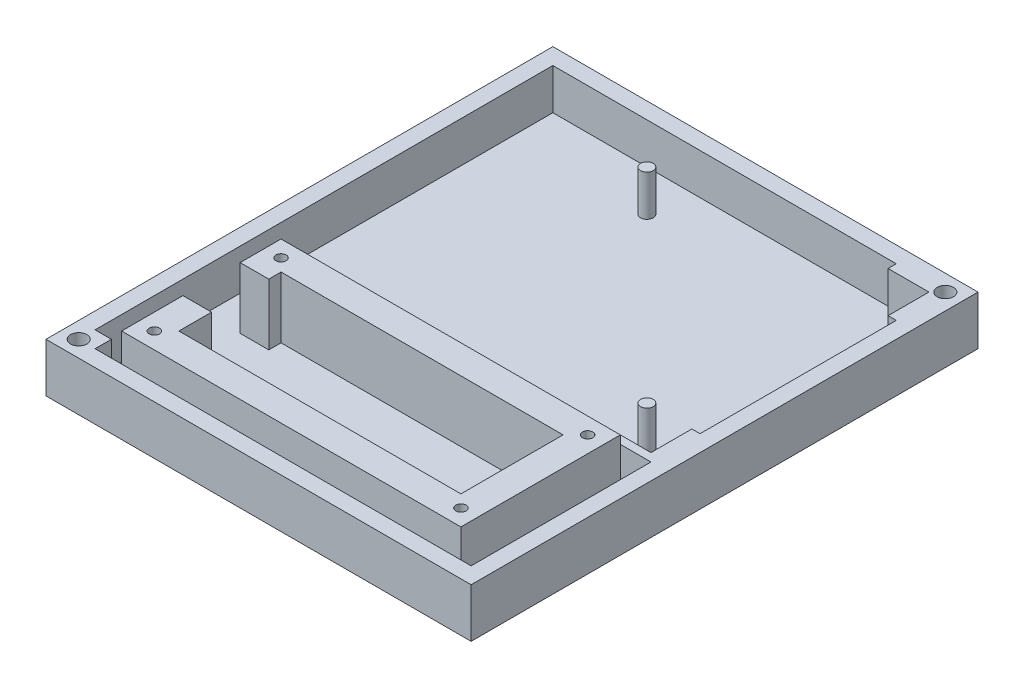
SolidWorks part; units mm, degrees
ref_plane "Front Plane" through (0, 0, 0) normal (0, 0, 1) x (1, 0, 0)
ref_plane "Top Plane" through (0, 0, 0) normal (0, 1, 0) x (1, 0, 0)
ref_plane "Right Plane" through (0, 0, 0) normal (1, 0, 0) x (0, 0, -1)
sketch "Sketch1" plane through (0, 0, 0) normal (0, 1, 0) x (1, 0, 0)
  line L1 (-52, -62) -> (52, -62)
  line L2 (-52, -62) -> (-52, 62)
  line L3 (-52, 62) -> (52, 62)
  line L4 (52, -62) -> (52, 62)
  line L5 (-52, -62) -> (52, 62) construction
  line L6 (-52, 62) -> (52, -62) construction
  point P0 (0, 0)
  dimension "D1" = 104
  dimension "D2" = 124
extrude "Boss-Extrude1" add sketch "Sketch1" along normal blind 2
sketch "Sketch2" plane through (0, 2, 0) normal (0, 1, 0) x (1, 0, 0)
  line L0 (48, -2) -> (46, -2)
  line L1 (46, -2) -> (46, -12)
  line L2 (46, -12) -> (36, -12)
  line L3 (36, -12) -> (36, -14)
  line L4 (48, 46) -> (46, 46)
  line L5 (46, 46) -> (46, 56)
  line L6 (46, 56) -> (36, 56)
  line L7 (36, 56) -> (36, 58)
  line L8 (48, -58) -> (48, 58)
  line L9 (48, 58) -> (-48, 58)
  line L10 (-48, 58) -> (-48, -58)
  line L11 (-48, -58) -> (48, -58)
  line L12 (48, -58) -> (48, 56)
  line L13 (46, 58) -> (-48, 58)
  line L14 (-48, 58) -> (-48, -54)
  line L15 (-44, -58) -> (48, -58)
  line L16 (36, -14) -> (48, -14)
  line L17 (-15, 48) -> (35, 48) construction
  line L18 (-15, 48) -> (-15, -2) construction
  line L19 (-15, -2) -> (35, -2) construction
  line L20 (35, 48) -> (35, -2) construction
  line L29 (-44, -58) -> (-44, -54)
  line L30 (-44, -54) -> (-48, -54)
  circle A0 centre (-15, 48) radius 1.55
  circle A1 centre (35, -2) radius 1.55
  circle A2 centre (-48, -58) radius 2
  circle A3 centre (48, 58) radius 2
  line M12 (52, -62) -> (52, 62)
  line M13 (52, 62) -> (-52, 62)
  line M14 (-52, 62) -> (-52, -62)
  line M15 (-52, -62) -> (52, -62)
  dimension "D1" = 3.1
  dimension "D13" = 4
  dimension "D15" = 4
  dimension "D2" = 50
  dimension "D3" = 8
  dimension "D5" = 11
  dimension "D6" = 2
  dimension "D7" = 2
  dimension "D8" = 10
  dimension "D9" = 10
  dimension "D10" = 2
  dimension "D11" = 2
  dimension "D12" = 10
  dimension "D14" = 4
  dimension "D16" = 10
  dimension "D4" = 4
extrude "Boss-Extrude2" add sketch "Sketch2" along normal blind 10 contours L15 L14 L13 L12 M15 M12 M13 M14 | A0 | L12 L13 L7 L6 L5 L4 | A1 | L3 L16 L12 L0 L1 L2
sketch "Sketch3" plane through (0, 2, 0) normal (0, 1, 0) x (1, 0, 0)
  line L0 (-32.5, -49) -> (-32.5, -24)
  line L1 (-35.5, -52) -> (39.5, -52) construction
  line L2 (-35.5, -52) -> (-35.5, -21) construction
  line L3 (-35.5, -21) -> (39.5, -21) construction
  line L4 (39.5, -52) -> (39.5, -21) construction
  line L5 (-32.5, -24) -> (36.5, -24)
  line L6 (36.5, -49) -> (36.5, -24)
  line L7 (-32.5, -49) -> (36.5, -49)
  line L8 (-39.5, -17) -> (43.5, -17)
  line L9 (43.5, -56) -> (43.5, -17)
  line L10 (-39.5, -56) -> (43.5, -56)
  line L11 (-39.5, -56) -> (-39.5, -17)
  line L12 (-44, -58) -> (48, -58) construction
  line L13 (-44, -58) -> (48, -58) construction
  line L14 (-32.5, -27) -> (-39.5, -27)
  line L15 (-32.5, -41) -> (-39.5, -41)
  circle A0 centre (-35.5, -21) radius 1.25
  circle A1 centre (39.5, -21) radius 1.25
  circle A2 centre (39.5, -52) radius 1.25
  circle A3 centre (-35.5, -52) radius 1.25
  point P17 (2, -21)
  point P19 (2, -58)
  dimension "D3" = 2.5
  dimension "D4" = 75
  dimension "D5" = 31
  dimension "D6" = 6
  dimension "D7" = 10
  dimension "D8" = 15
  dimension "D1" = 3
  dimension "D2" = 4
extrude "Boss-Extrude3" add sketch "Sketch3" along normal blind 15 contours L0 L15 L11 L10 L9 L8 L14 L5 L6 L7 A3 A2 A1 A0
